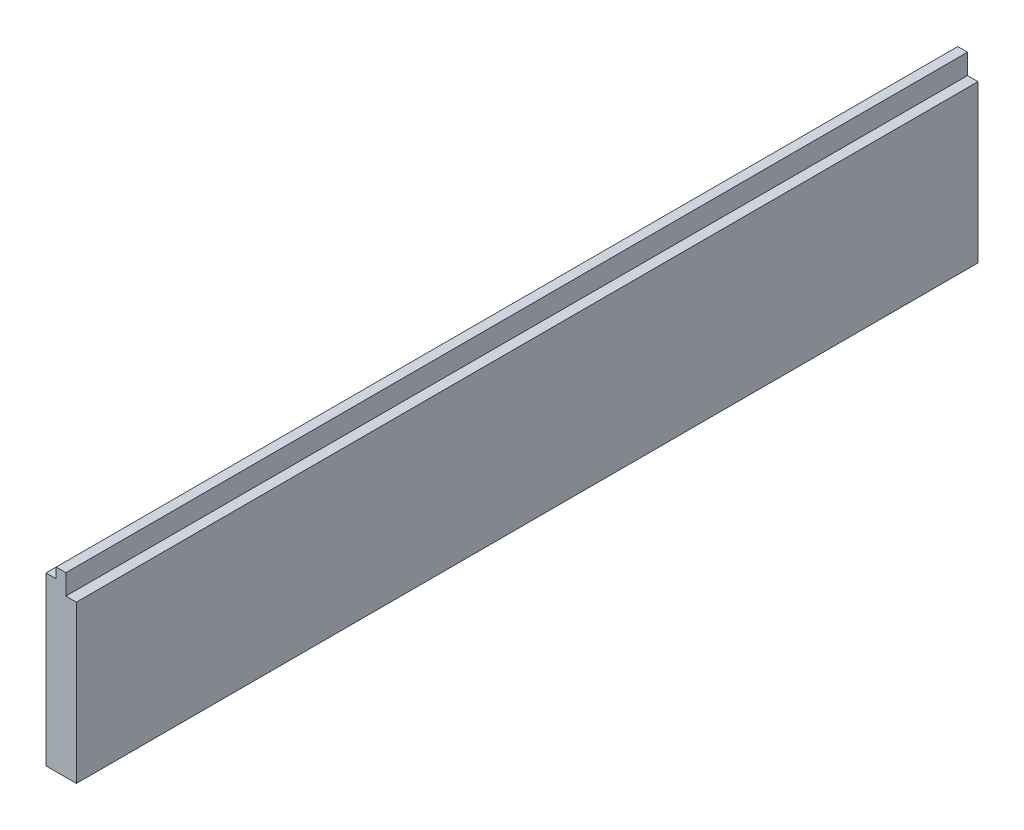
SolidWorks part; units mm, degrees
material "Сосна"
ref_plane "Спереди" through (0, 0, 0) normal (0, 0, 1) x (1, 0, 0)
ref_plane "Сверху" through (0, 0, 0) normal (0, 1, 0) x (1, 0, 0)
ref_plane "Справа" through (0, 0, 0) normal (1, 0, 0) x (0, 0, -1)
sketch "Эскиз1" plane through (0, 0, 0) normal (0, 0, 1) x (1, 0, 0)
  line L0 (0, 0) -> (30, 0)
  line L3 (30, 0) -> (30, 155)
  line L4 (30, 155) -> (19.6619, 155)
  line L5 (10, 175) -> (10, 165)
  line L6 (10, 165) -> (0, 165)
  line L7 (0, 165) -> (0, 0)
  line L8 (19.6619, 175) -> (10, 175)
  line L9 (19.6619, 155) -> (19.6619, 175)
  dimension "D1" = 155
  dimension "D2" = 30
  dimension "D3" = 10
  dimension "D4" = 20
  dimension "D5" = 10
extrude "Бобышка-Вытянуть1" add sketch "Эскиз1" along normal blind 890
